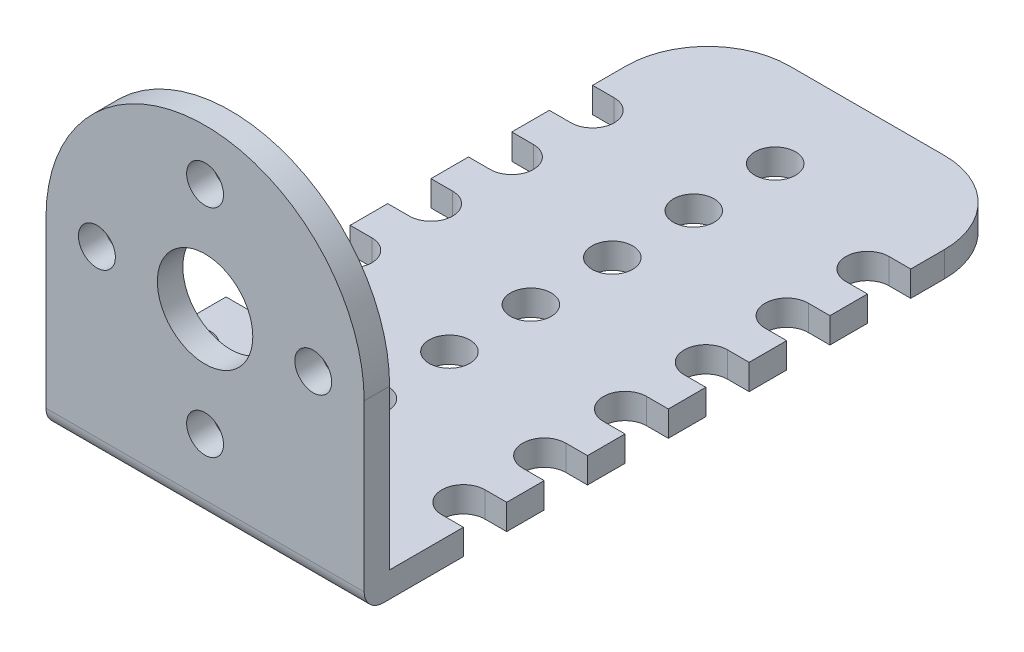
SolidWorks part; units mm, degrees
ref_plane "Front Plane" through (0, 0, 0) normal (0, 0, 1) x (1, 0, 0)
ref_plane "Top Plane" through (0, 0, 0) normal (0, 1, 0) x (1, 0, 0)
ref_plane "Right Plane" through (0, 0, 0) normal (1, 0, 0) x (0, 0, -1)
sketch "Sketch1" plane through (0, 0, 0) normal (1, 0, 0) x (0, 0, -1)
  line L0 (0, 25) -> (0, 0)
  line L1 (0, 0) -> (50, 0)
  line L2 (50, 0) -> (50, -2)
  line L3 (50, -2) -> (-2, -2)
  line L4 (-2, -2) -> (-2, 25)
  line L5 (-2, 25) -> (0, 25)
  dimension "D1" = 50
  dimension "D2" = 2
  dimension "D3" = 2
  dimension "D4" = 25
extrude "Boss-Extrude1" add sketch "Sketch1" along normal mid plane 25
fillet "Fillet1" radius 1.5 1 edges at (0, -2, 2)
sketch "Sketch3" plane through (0, 0, 2) normal (0, 0, 1) x (1, 0, 0)
  line L0 (12.5, 25) -> (12.5, -0.5) construction
  line L1 (-12.5, 25) -> (-12.5, -0.5) construction
  line L3 (12.5, 25) -> (-12.5, 25) construction
  line L4 (12.5, -2) -> (-12.5, -2) construction
  circle A0 centre (0, 12.5) radius 12.5
  circle A1 centre (0, 12.5) radius 8.5 construction
  circle A2 centre (0, 12.5) radius 3.75
  circle A3 centre (0, 21) radius 1.45
  circle A4 centre (8.5, 12.5) radius 1.45
  circle A5 centre (0, 4) radius 1.45
  circle A6 centre (-8.5, 12.5) radius 1.45
  point P21 (0, 12.5)
  line M1 (-12.5, 25) -> (-12.5, -0.5)
  line M3 (12.5, -0.5) -> (12.5, 25)
  line M4 (12.5, 25) -> (-12.5, 25)
  dimension "D1" = 17
  dimension "D2" = 7.5
  dimension "D3" = 2.9
  dimension "D5" = 14.5
  dimension "D4" = 4
extrude "Cut-Extrude1" cut sketch "Sketch3" against normal through all contours A0 M4 M1 | A0 M3 M4 | A3 | A2 | A6 | A5 | A4
sketch "Sketch5" plane through (0, -2, 0) normal (0, -1, 0) x (1, 0, 0)
  line L0 (0, 0) -> (0, -50) construction
  line L1 (12.5, -50) -> (-12.5, -50) construction
  line L3 (-12.5, 2) -> (12.5, 2) construction
  circle A0 centre (0, -42.8) radius 1.6
  circle A1 centre (0, -36.4) radius 1.6
  circle A2 centre (0, -30) radius 1.6
  circle A3 centre (0, -23.6) radius 1.6
  circle A4 centre (0, -17.2) radius 1.6
  circle A5 centre (0, -10.8) radius 1.6
  circle A6 centre (0, -4.4) radius 1.6
  dimension "D1" = 3.2
  dimension "D2" = 6.4
  dimension "D4" = 6.4
  dimension "D3" = 7
extrude "Cut-Extrude2" cut sketch "Sketch5" against normal through all
sketch "Sketch6" plane through (0, -2, 0) normal (0, -1, 0) x (1, 0, 0)
  line L0 (12.5, -50) -> (-12.5, -50) construction
  line L1 (10.8, -40.95) -> (12.5, -40.95)
  line L2 (12.5, 0.5) -> (12.5, -50) construction
  line L3 (10.8, -37.55) -> (12.5, -37.55)
  line L4 (10.8, -34.6) -> (12.5, -34.6)
  line L5 (10.8, -31.2) -> (12.5, -31.2)
  line L6 (10.8, -28.25) -> (12.5, -28.25)
  line L7 (10.8, -24.85) -> (12.5, -24.85)
  line L8 (10.8, -21.9) -> (12.5, -21.9)
  line L9 (10.8, -18.5) -> (12.5, -18.5)
  line L10 (10.8, -15.55) -> (12.5, -15.55)
  line L11 (10.8, -12.15) -> (12.5, -12.15)
  line L12 (12.5, -50) -> (12.5, 0) construction
  line L13 (10.8, -9.2) -> (12.5, -9.2)
  line L14 (10.8, -5.8) -> (12.5, -5.8)
  line L15 (-12.5, 2) -> (12.5, 2) construction
  circle A0 centre (10.8, -39.25) radius 1.7
  circle A1 centre (10.8, -32.9) radius 1.7
  circle A2 centre (10.8, -26.55) radius 1.7
  circle A3 centre (10.8, -20.2) radius 1.7
  circle A4 centre (10.8, -13.85) radius 1.7
  circle A5 centre (10.8, -7.5) radius 1.7
  circle M20 centre (0, -10.8) radius 1.6
  line M22 (12.5, -50) -> (12.5, 0.5)
  dimension "D3" = 3.4
  dimension "D1" = 10.75
  dimension "D2" = 10.8
  dimension "D5" = 6.35
  dimension "D6" = 9.5
  dimension "D4" = 6
extrude "Cut-Extrude3" cut sketch "Sketch6" against normal through all contours A5 L14 M22 | A5 | A5 L13 M22 | A4 L11 M22 | A4 | A4 L10 M22 | A3 L9 M22 | A3 | A3 L8 M22 | A2 L7 M22 | A2 | A2 L6 M22 | A1 L5 M22 | A1 L4 M22 | A0 L3 M22 | A0 L1 M22 | A0 M20
mirror "Mirror1" about plane through (0, 0, 0) normal (1, 0, 0) of "Cut-Extrude3"
fillet "Fillet2" radius 6.4 2 edges at (-12.5, -1, -50) (12.5, -1, -50)
